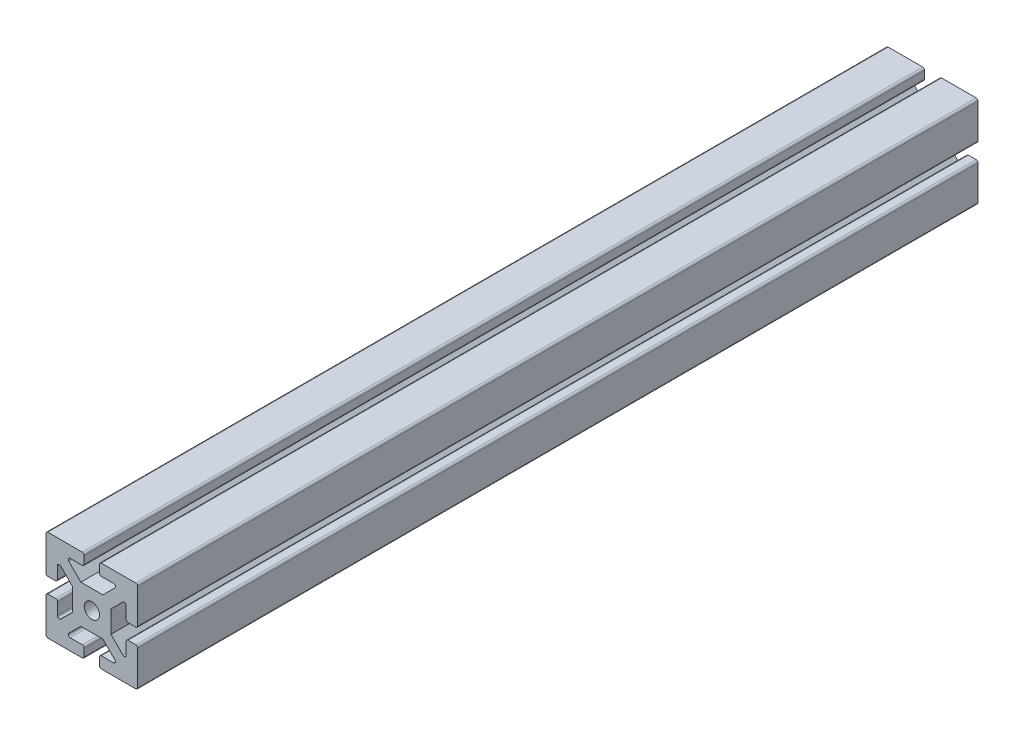
SolidWorks part; units mm, degrees
ref_plane "Front Plane" through (0, 0, 0) normal (0, 0, 1) x (1, 0, 0)
ref_plane "Top Plane" through (0, 0, 0) normal (0, 1, 0) x (1, 0, 0)
ref_plane "Right Plane" through (0, 0, 0) normal (1, 0, 0) x (0, 0, -1)
sketch "Sketch1" plane through (0, 0, 0) normal (0, 0, 1) x (1, 0, 0)
  line L0 (3.0126, 4.0732) -> (1.4393, 2.5)
  line L1 (-5.75, -6) -> (-1.25, -6)
  line L2 (-6, -5.75) -> (-6, -1.25)
  line L3 (-5.75, 6) -> (-1.25, 6)
  line L4 (6, -5.75) -> (6, -1.25)
  line L5 (-6, -6) -> (6, 6) construction
  line L6 (-6, 6) -> (6, -6) construction
  line L7 (4.0732, 3.0126) -> (2.5, 1.4393)
  line L8 (2.8358, 4.5) -> (1.25, 4.5)
  line L9 (4.5, 2.8358) -> (4.5, 1.25)
  line L10 (1, 4.75) -> (1, 5.75)
  line L11 (-1.4393, -2.5) -> (1.4393, -2.5)
  line L12 (-2.5, -1.4393) -> (-2.5, 1.4393)
  line L13 (-1.4393, 2.5) -> (1.4393, 2.5)
  line L14 (2.5, -1.4393) -> (2.5, 1.4393)
  line L15 (-2.5, -2.5) -> (2.5632, 2.5632) construction
  line L16 (-2.5, 2.5) -> (2.5, -2.5) construction
  line L17 (4.75, 1) -> (5.75, 1)
  line L18 (1, -4.75) -> (1, -5.75)
  line L19 (2.8358, -4.5) -> (1.25, -4.5)
  line L20 (3.0126, -4.0732) -> (1.4393, -2.5)
  line L21 (4.0732, -3.0126) -> (2.5, -1.4393)
  line L22 (4.5, -2.8358) -> (4.5, -1.25)
  line L23 (4.75, -1) -> (5.75, -1)
  line L24 (-4.75, -1) -> (-5.75, -1)
  line L25 (-4.5, -2.8358) -> (-4.5, -1.25)
  line L26 (-4.0732, -3.0126) -> (-2.5, -1.4393)
  line L27 (-3.0126, -4.0732) -> (-1.4393, -2.5)
  line L28 (-2.8358, -4.5) -> (-1.25, -4.5)
  line L29 (-1, -4.75) -> (-1, -5.75)
  line L30 (-1, 4.75) -> (-1, 5.75)
  line L31 (-2.8358, 4.5) -> (-1.25, 4.5)
  line L32 (-3.0126, 4.0732) -> (-1.4393, 2.5)
  line L33 (-4.0732, 3.0126) -> (-2.5, 1.4393)
  line L34 (-4.5, 2.8358) -> (-4.5, 1.25)
  line L35 (-4.75, 1) -> (-5.75, 1)
  line L36 (6, 1.25) -> (6, 5.75)
  line L37 (1.25, 6) -> (5.75, 6)
  line L38 (-6, 1.25) -> (-6, 5.75)
  line L39 (1.25, -6) -> (5.75, -6)
  circle A0 centre (0, 0) radius 1
  arc A1 (-4.5, -2.8358) -> (-4.0732, -3.0126) centre (-4.25, -2.8358) ccw
  arc A2 (-4.75, -1) -> (-4.5, -1.25) centre (-4.75, -1.25) cw
  arc A3 (-5.75, -1) -> (-6, -1.25) centre (-5.75, -1.25) ccw
  arc A4 (-2.8358, -4.5) -> (-3.0126, -4.0732) centre (-2.8358, -4.25) cw
  arc A5 (-1.25, -4.5) -> (-1, -4.75) centre (-1.25, -4.75) cw
  arc A6 (-1, -5.75) -> (-1.25, -6) centre (-1.25, -5.75) cw
  arc A7 (-5.75, -6) -> (-6, -5.75) centre (-5.75, -5.75) cw
  arc A8 (-6, 5.75) -> (-5.75, 6) centre (-5.75, 5.75) cw
  arc A9 (5.75, 6) -> (6, 5.75) centre (5.75, 5.75) cw
  arc A10 (5.75, -6) -> (6, -5.75) centre (5.75, -5.75) ccw
  arc A11 (4.0732, -3.0126) -> (4.5, -2.8358) centre (4.25, -2.8358) ccw
  arc A12 (2.8358, -4.5) -> (3.0126, -4.0732) centre (2.8358, -4.25) ccw
  arc A13 (1, -4.75) -> (1.25, -4.5) centre (1.25, -4.75) cw
  arc A14 (5.75, -1) -> (6, -1.25) centre (5.75, -1.25) cw
  arc A15 (4.5, -1.25) -> (4.75, -1) centre (4.75, -1.25) cw
  arc A16 (5.75, 1) -> (6, 1.25) centre (5.75, 1.25) ccw
  arc A17 (4.5, 1.25) -> (4.75, 1) centre (4.75, 1.25) ccw
  arc A18 (4.0732, 3.0126) -> (4.5, 2.8358) centre (4.25, 2.8358) cw
  arc A19 (3.0126, 4.0732) -> (2.8358, 4.5) centre (2.8358, 4.25) ccw
  arc A20 (-2.8358, 4.5) -> (-3.0126, 4.0732) centre (-2.8358, 4.25) ccw
  arc A21 (-4.0732, 3.0126) -> (-4.5, 2.8358) centre (-4.25, 2.8358) ccw
  arc A22 (-5.75, 1) -> (-6, 1.25) centre (-5.75, 1.25) cw
  arc A23 (-4.5, 1.25) -> (-4.75, 1) centre (-4.75, 1.25) cw
  arc A24 (-1, 5.75) -> (-1.25, 6) centre (-1.25, 5.75) ccw
  arc A25 (-1, 4.75) -> (-1.25, 4.5) centre (-1.25, 4.75) cw
  arc A26 (1.25, 4.5) -> (1, 4.75) centre (1.25, 4.75) cw
  arc A27 (1, 5.75) -> (1.25, 6) centre (1.25, 5.75) cw
  arc A28 (1, -5.75) -> (1.25, -6) centre (1.25, -5.75) ccw
  point P0 (0, 0)
  point P18 (0.5216, -3.6372)
  point P19 (-2.749, -0.7073)
  point P22 (0.3399, -3.4328)
  point P47 (0, 0)
  point P48 (4.1784, 7.492)
  point P85 (6, 1)
  point P88 (4.5, 1)
  point P107 (1, 4.5)
  point P110 (1, 6)
  dimension "D11" = 2
  dimension "D4" = 0.25
  dimension "D10" = 2
  dimension "D13" = 0.25
  dimension "D2" = 12
  dimension "D3" = 2.5
  dimension "D5" = 1.5
  dimension "D6" = 1.5
  dimension "D7" = 1.5
  dimension "D8" = 1
  dimension "D9" = 1
  dimension "D12" = 4
extrude "Boss-Extrude1" add sketch "Sketch1" against normal blind 110
